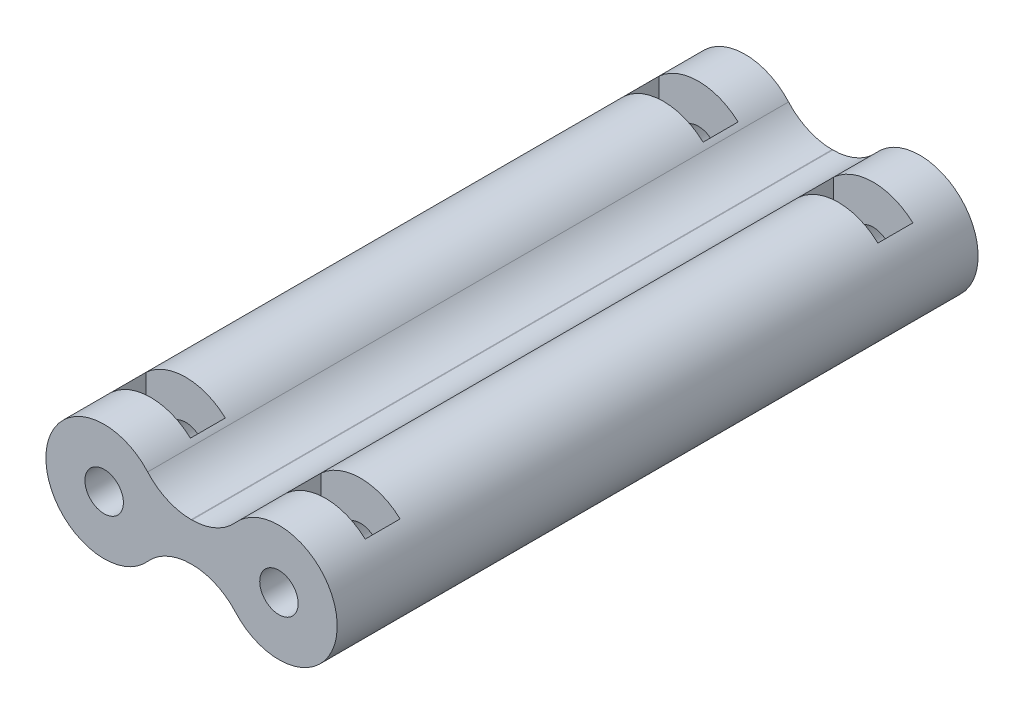
SolidWorks part; units mm, degrees
material "ABS"
ref_plane "Plano frontal" through (0, 0, 0) normal (0, 0, 1) x (1, 0, 0)
ref_plane "Plano superior" through (0, 0, 0) normal (0, 1, 0) x (1, 0, 0)
ref_plane "Plano direito" through (0, 0, 0) normal (1, 0, 0) x (0, 0, -1)
sketch "Esboço1" plane through (0, 0, 0) normal (0, 0, 1) x (1, 0, 0)
  line L0 (0, 0) -> (0, 3.1709) construction
  line L1 (-2.7801, 1.65) -> (2.7801, 1.65)
  line L2 (-2.7801, -1.65) -> (2.7801, -1.65)
  circle A0 centre (-7.5, 0) radius 1.65
  circle A1 centre (7.5, 0) radius 1.65
  arc A2 (-2.7801, 1.65) -> (-2.7801, -1.65) centre (-7.5, 0) ccw
  arc A3 (2.7801, -1.65) -> (2.7801, 1.65) centre (7.5, 0) ccw
  dimension "D1" = 3.3
  dimension "D3" = 10
  dimension "D2" = 15
extrude "Ressalto-extrusão1" add sketch "Esboço1" along normal blind 55
fillet "Filete1" radius 5 4 edges at (-2.7801, -1.65, 27.5) (2.7801, -1.65, 27.5) (2.7801, 1.65, 27.5) (-2.7801, 1.65, 27.5)
sketch "Esboço2" plane through (0, 0, 0) normal (0, 1, 0) x (1, 0, 0)
  line L0 (-7.5, 0) -> (-7.5, -55) construction
  line L1 (-5.85, 0) -> (-9.15, 0) construction
  line L2 (-12.5, -55) -> (-3.7658, -55) construction
  line L3 (-3.7658, 0) -> (-12.5, 0) construction
  line L4 (-10.9, -4) -> (-4.1, -4)
  line L5 (-10.9, -4) -> (-10.9, -7)
  line L6 (-10.9, -7) -> (-4.1, -7)
  line L7 (-4.1, -4) -> (-4.1, -7)
  line L8 (-10.9, -4) -> (-4.1, -7) construction
  line L9 (-10.9, -7) -> (-4.1, -4) construction
  line L10 (0, 0) -> (0, -55) construction
  line L11 (0.0316, -55) -> (-0.0316, -55) construction
  line L12 (-12.5, -27.5) -> (12.5, -27.5) construction
  line L13 (-12.5, 0) -> (-12.5, -55) construction
  line L14 (12.5, -55) -> (12.5, 0) construction
  line L15 (10.9, -7) -> (4.1, -4) construction
  line L16 (10.9, -4) -> (4.1, -7) construction
  line L17 (4.1, -4) -> (4.1, -7)
  line L18 (10.9, -7) -> (4.1, -7)
  line L19 (10.9, -4) -> (10.9, -7)
  line L20 (10.9, -4) -> (4.1, -4)
  line L21 (10.9, -51) -> (4.1, -48) construction
  line L22 (10.9, -48) -> (4.1, -51) construction
  line L23 (-10.9, -48) -> (-4.1, -51) construction
  line L24 (-10.9, -51) -> (-4.1, -48) construction
  line L25 (10.9, -51) -> (4.1, -51)
  line L26 (10.9, -51) -> (10.9, -48)
  line L27 (10.9, -48) -> (4.1, -48)
  line L28 (4.1, -51) -> (4.1, -48)
  line L29 (-4.1, -51) -> (-4.1, -48)
  line L30 (-10.9, -48) -> (-4.1, -48)
  line L31 (-10.9, -51) -> (-10.9, -48)
  line L32 (-10.9, -51) -> (-4.1, -51)
  point P6 (-7.5, -5.5)
  point P28 (7.5, -5.5)
  point P37 (7.5, -49.5)
  point P38 (-7.5, -49.5)
  dimension "D1" = 3
  dimension "D2" = 6.8
  dimension "D3" = 4
extrude "Corte-extrusão1" cut sketch "Esboço2" against normal through all both and the other way through all contours L7 L4 L5 L6 | L19 L20 L17 L18 | L28 L25 L26 L27 | L31 L32 L29 L30
